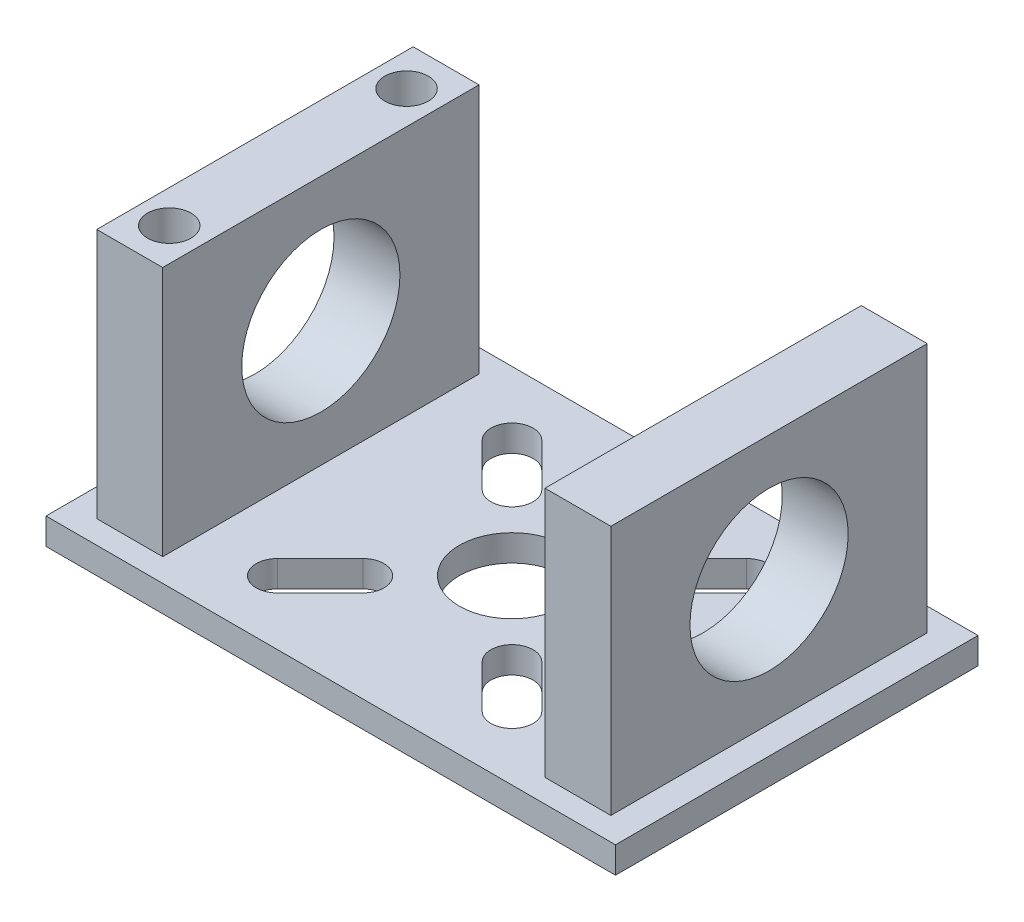
SolidWorks part; units mm, degrees
ref_plane "前视基准面" through (0, 0, 0) normal (0, 0, 1) x (1, 0, 0)
ref_plane "上视基准面" through (0, 0, 0) normal (0, 1, 0) x (1, 0, 0)
ref_plane "右视基准面" through (0, 0, 0) normal (1, 0, 0) x (0, 0, -1)
sketch "草图1" plane through (0, 0, 0) normal (0, 1, 0) x (1, 0, 0)
  line L1 (-21.6, -13.75) -> (21.6, -13.75)
  line L2 (-21.6, -13.75) -> (-21.6, 13.75)
  line L3 (-21.6, 13.75) -> (21.6, 13.75)
  line L4 (21.6, -13.75) -> (21.6, 13.75)
  line L5 (-21.6, -13.75) -> (21.6, 13.75) construction
  line L6 (-21.6, 13.75) -> (21.6, -13.75) construction
  point P0 (0, 0)
  dimension "D1" = 27.5
  dimension "D2" = 43.2
extrude "凸台-拉伸1" add sketch "草图1" along normal blind 2
sketch "草图2" plane through (0, 2, 0) normal (0, 1, 0) x (1, 0, 0)
  line L1 (17, -9) -> (-17, -9) construction
  line L2 (17, -9) -> (17, 9) construction
  line L3 (17, 9) -> (-17, 9) construction
  line L4 (-17, -9) -> (-17, 9) construction
  line L5 (17, -9) -> (-17, 9) construction
  line L6 (17, 9) -> (-17, -9) construction
  circle A0 centre (-17, 9) radius 1.65
  point P0 (0, 0)
  dimension "D3" = 3.3
  dimension "D1" = 34
  dimension "D2" = 18
extrude "切除-拉伸1" cut sketch "草图2" against normal up to next
sketch "草图3" plane through (0, 2, 0) normal (0, 1, 0) x (1, 0, 0)
  line L0 (0, 13.75) -> (0, -13.75) construction
  line L1 (21.6, 13.75) -> (-21.6, 13.75) construction
  line L2 (-21.6, -13.75) -> (21.6, -13.75) construction
  line L3 (0, 0) -> (-5.6569, 5.6569) construction
  line L4 (-5.6569, 5.6569) -> (-8.9025, 8.9025) construction
  line L5 (-6.7882, 4.5255) -> (-10.0338, 7.7711)
  line L6 (-4.5255, 6.7882) -> (-7.7711, 10.0338)
  arc A0 (-6.7882, 4.5255) -> (-4.5255, 6.7882) centre (-5.6569, 5.6569) ccw
  arc A1 (-7.7711, 10.0338) -> (-10.0338, 7.7711) centre (-8.9025, 8.9025) ccw
  point P9 (-7.2797, 7.2797)
  dimension "D4" = 1.6
  dimension "D1" = 45
  dimension "D2" = 8
  dimension "D3" = 4.59
extrude "切除-拉伸2" cut sketch "草图3" against normal up to next
mirror "镜向1" about plane through (0, 0, 0) normal (0, 0, 1) of "切除-拉伸2", "切除-拉伸1"
mirror "镜向2" about plane through (0, 0, 0) normal (1, 0, 0) of "镜向1", "切除-拉伸1", "切除-拉伸2"
sketch "草图4" plane through (0, 2, 0) normal (0, 1, 0) x (1, 0, 0)
  circle A0 centre (0, 0) radius 4
  dimension "D1" = 8
extrude "切除-拉伸3" cut sketch "草图4" against normal up to next
sketch "草图5" plane through (0, 2, 0) normal (0, 1, 0) x (1, 0, 0)
  line L0 (-17, 9) -> (-17, -9) construction
  line L2 (-19.5, -12) -> (-14.5, -12)
  line L3 (-19.5, -12) -> (-19.5, 12)
  line L4 (-19.5, 12) -> (-14.5, 12)
  line L5 (-14.5, -12) -> (-14.5, 12)
  line L6 (-19.5, -12) -> (-14.5, 12) construction
  line L7 (-19.5, 12) -> (-14.5, -12) construction
  point P4 (-17, 0)
  dimension "D1" = 5
  dimension "D2" = 24
extrude "凸台-拉伸2" add sketch "草图5" along normal blind 19
sketch "草图6" plane through (-19.5, 0, 0) normal (-1, 0, 0) x (0, 0, 1)
  line L0 (0, 21) -> (0, 2) construction
  line L1 (-12, 21) -> (12, 21) construction
  line L2 (-13.75, 2) -> (13.75, 2) construction
  circle A0 centre (0, 11.5) radius 6
  dimension "D1" = 12
extrude "切除-拉伸5" cut sketch "草图6" against normal up to next
sketch "草图7" plane through (0, 0, 0) normal (0, -1, 0) x (1, 0, 0)
  circle A0 centre (-17, 9) radius 1.65
  circle A1 centre (-17, -9) radius 1.65
  circle A2 centre (-17, 9) radius 1.65 construction
  circle A3 centre (-17, -9) radius 1.65 construction
extrude "切除-拉伸6" cut sketch "草图7" against normal up to next
mirror "镜向3" about plane through (0, 0, 0) normal (1, 0, 0) of "切除-拉伸1", "切除-拉伸5", "凸台-拉伸2"
